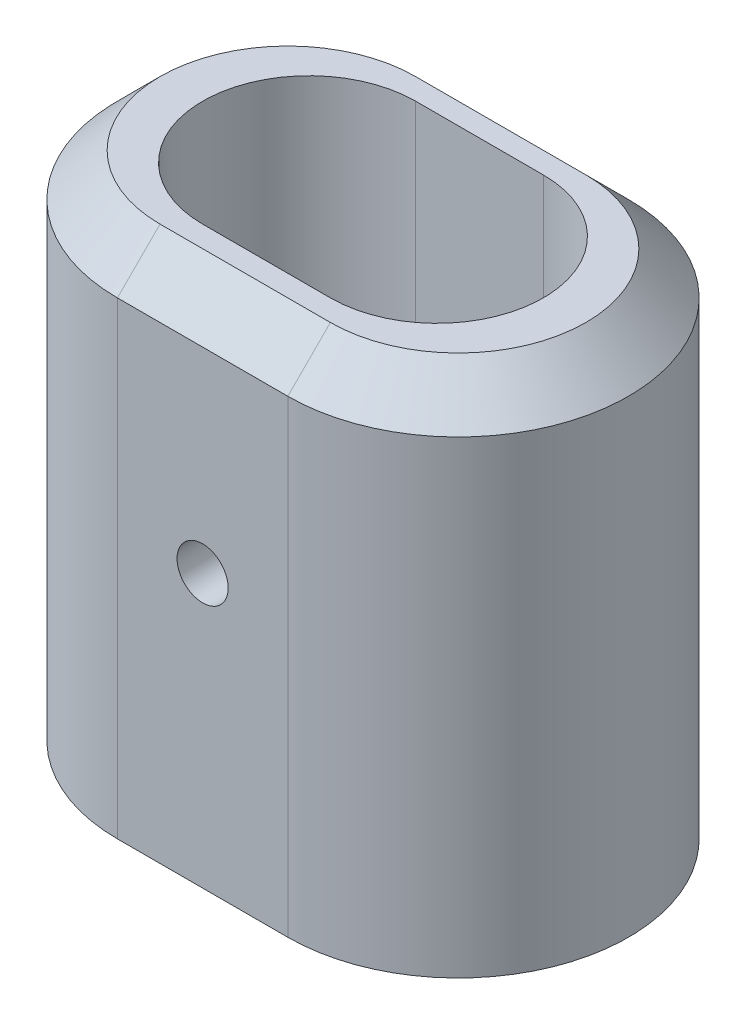
SolidWorks part; units mm, degrees
material "Tungsten"
ref_plane "Front Plane" through (0, 0, 0) normal (0, 0, 1) x (1, 0, 0)
ref_plane "Top Plane" through (0, 0, 0) normal (0, 1, 0) x (1, 0, 0)
ref_plane "Right Plane" through (0, 0, 0) normal (1, 0, 0) x (0, 0, -1)
sketch "Sketch1" plane through (0, 0, 0) normal (0, 1, 0) x (1, 0, 0)
  line L0 (-10, 20) -> (10, 20)
  line L1 (10, -20) -> (-10, -20)
  line L3 (-7.5, 12.5) -> (7.5, 12.5)
  line L4 (-7.5, -12.5) -> (7.5, -12.5)
  arc A2 (-7.5, 12.5) -> (-7.5, -12.5) centre (-7.5, 0) ccw
  arc A3 (7.5, 12.5) -> (7.5, -12.5) centre (7.5, 0) cw
  arc A4 (10, 20) -> (10, -20) centre (10, 0) cw
  arc A5 (-10, 20) -> (-10, -20) centre (-10, 0) ccw
  point P3 (-20, 0)
  point P4 (20, 0)
  point P11 (0, 20)
  point P14 (0, 12.5)
  point P17 (0, -20)
  point P18 (30, 0)
  point P19 (-30, 0)
  dimension "D1" = 40
  dimension "D4" = 20
  dimension "D2" = 25
  dimension "D5" = 20
  dimension "D6" = 60
extrude "Boss-Extrude1" add sketch "Sketch1" along normal blind 60
chamfer "Chamfer1" distance 5 angle 45 4 edges at (30, 60, 0) (0, 60, -20) (0, 60, 20) (-30, 60, 0)
sketch "Sketch2" plane through (0, 0, 12.5) normal (0, 0, -1) x (-1, 0, 0)
  line L0 (0, 60) -> (0, 32) construction
  line L1 (-10, 60) -> (10, 60) construction
  circle A0 centre (0, 32) radius 3
  dimension "D1" = 6
  dimension "D2" = 28
extrude "Cut-Extrude1" cut sketch "Sketch2" against normal through all and the other way through all
